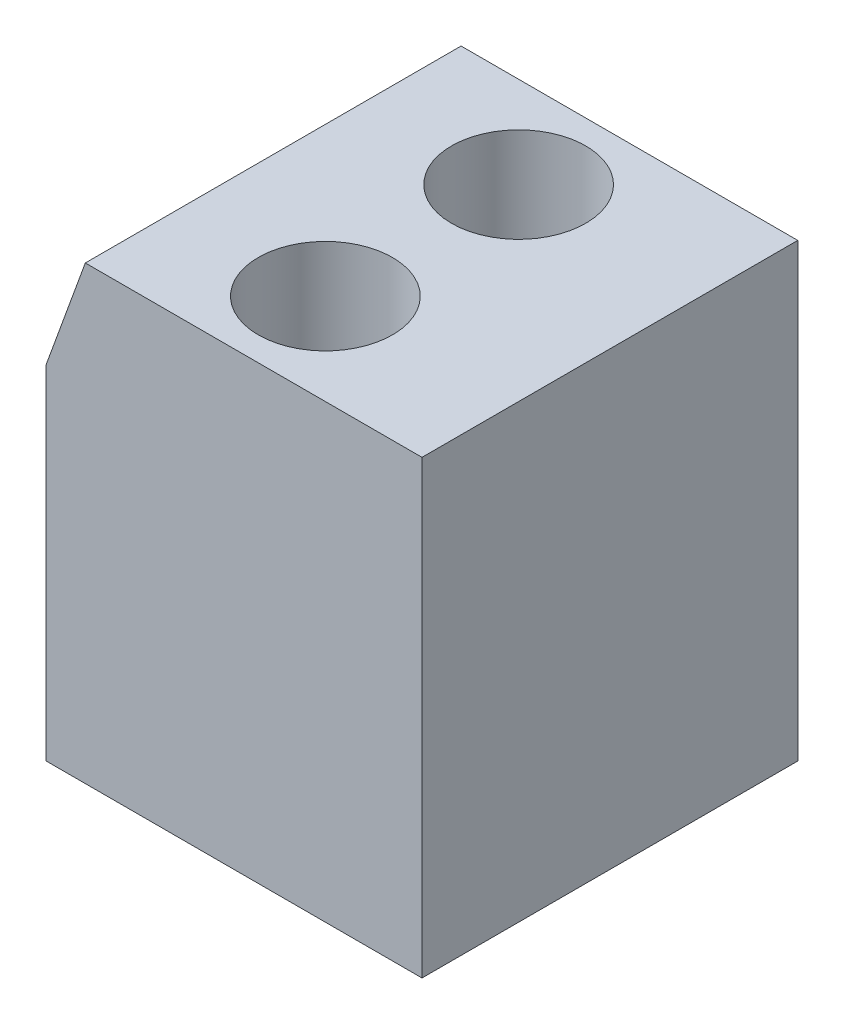
SolidWorks part; units mm, degrees
ref_plane "Plan de face" through (0, 0, 0) normal (0, 0, 1) x (1, 0, 0)
ref_plane "Plan de dessus" through (0, 0, 0) normal (0, 1, 0) x (1, 0, 0)
ref_plane "Plan de droite" through (0, 0, 0) normal (1, 0, 0) x (0, 0, -1)
sketch "Esquisse1" plane through (0, 0, 0) normal (0, 1, 0) x (1, 0, 0)
  line L1 (0, 0) -> (7, 0)
  line L2 (0, 0) -> (0, -7)
  line L3 (0, -7) -> (7, -7)
  line L4 (7, 0) -> (7, -7)
  dimension "D1" = 7
  dimension "D2" = 7
extrude "Boss.-Extru.1" add sketch "Esquisse1" along normal blind 8.4
chamfer "Chanfrein1" distance 2 angle 20 1 edges at (0, 8.4, 3.5)
sketch "Esquisse2" plane through (0, 8.4, 0) normal (0, 1, 0) x (1, 0, 0)
  line L0 (7, -7) -> (7, 0) construction
  line L1 (7, 0) -> (0.7279, 0) construction
  line L2 (0.7279, -7) -> (7, -7) construction
  circle A0 centre (3.5, -1.7) radius 1.25
  circle A1 centre (3.5, -5.3) radius 1.25
  dimension "D1" = 2.5
  dimension "D2" = 3.5
  dimension "D3" = 1.7
  dimension "D4" = 1.7
extrude "Enlèv. mat.-Extru.1" cut sketch "Esquisse2" against normal blind 4
